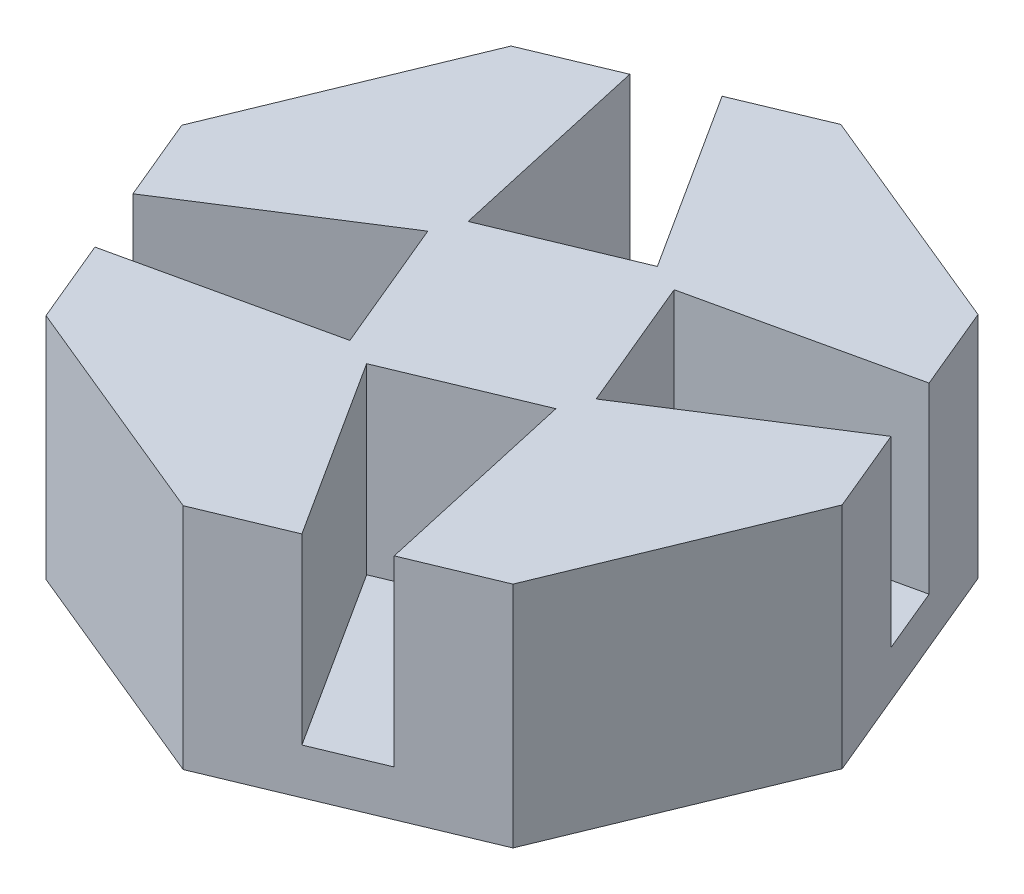
SolidWorks part; units mm, degrees
ref_plane "Front Plane" through (0, 0, 0) normal (0, 0, 1) x (1, 0, 0)
ref_plane "Top Plane" through (0, 0, 0) normal (0, 1, 0) x (1, 0, 0)
ref_plane "Right Plane" through (0, 0, 0) normal (1, 0, 0) x (0, 0, -1)
sketch "Sketch1" plane through (0, 0, 0) normal (0, 1, 0) x (1, 0, 0)
  line L1 (-0.112, 54.9379) -> (-38.9262, 38.7678)
  line L2 (-38.9262, 38.7678) -> (-54.9379, -0.112)
  line L3 (-54.9379, -0.112) -> (-38.7678, -38.9262)
  line L4 (-38.7678, -38.9262) -> (0.112, -54.9379)
  line L5 (0.112, -54.9379) -> (38.9262, -38.7678)
  line L6 (38.9262, -38.7678) -> (54.9379, 0.112)
  line L7 (54.9379, 0.112) -> (38.7678, 38.9262)
  line L8 (38.7678, 38.9262) -> (-0.112, 54.9379)
  circle A0 centre (0, 0) radius 50.7561 construction
  dimension "D2" = 101.5123
  dimension "D1" = 38.8798
  dimension "D3" = 42.0478
extrude "Boss-Extrude1" add sketch "Sketch1" along normal blind 38.1
sketch "Sketch2" plane through (0, 38.1, 0) normal (0, 1, 0) x (1, 0, 0)
  line L0 (19.5191, -46.8529) -> (6.0393, -14.4964) construction
  line L1 (-5.0979, -19.1362) -> (14.0872, -49.1158)
  line L2 (0.112, -54.9379) -> (38.9262, -38.7678) construction
  line L3 (17.1764, -9.8567) -> (24.9509, -44.5899)
  line L4 (-5.0979, -19.1362) -> (17.1764, -9.8567)
  line L5 (-19.1362, 5.0979) -> (-49.1158, -14.0872)
  line L6 (-19.1362, 5.0979) -> (-9.8567, -17.1764)
  line L7 (-9.8567, -17.1764) -> (-44.5899, -24.9509)
  line L8 (-46.8529, -19.5191) -> (-14.4964, -6.0393) construction
  line L9 (5.0979, 19.1362) -> (-14.0872, 49.1158)
  line L10 (5.0979, 19.1362) -> (-17.1764, 9.8567)
  line L11 (-17.1764, 9.8567) -> (-24.9509, 44.5899)
  line L12 (-19.5191, 46.8529) -> (-6.0393, 14.4964) construction
  line L13 (19.1362, -5.0979) -> (49.1158, 14.0872)
  line L14 (19.1362, -5.0979) -> (9.8567, 17.1764)
  line L15 (9.8567, 17.1764) -> (44.5899, 24.9509)
  line L16 (46.8529, 19.5191) -> (14.4964, 6.0393) construction
  point P30 (0, 0)
  line M17 (-0.112, 54.9379) -> (-38.9262, 38.7678)
  line M19 (-54.9379, -0.112) -> (-38.7678, -38.9262)
  line M21 (0.112, -54.9379) -> (38.9262, -38.7678)
  line M23 (54.9379, 0.112) -> (38.7678, 38.9262)
  dimension "D1" = 14.4964
  dimension "D2" = 24.13
  dimension "D3" = 35.052
  dimension "D4" = 80
  dimension "D5" = 80
  dimension "D6" = 4
  dimension "D7" = 14.4964
  dimension "D8" = 5.1465
extrude "Cut-Extrude1" cut sketch "Sketch2" along direction (0, 1, 0) on the side against the normal blind 30.48 contours L4 L1 L3 M21 | L7 L6 L5 M19 | L11 L10 L9 M17 | L15 L14 L13 M23
